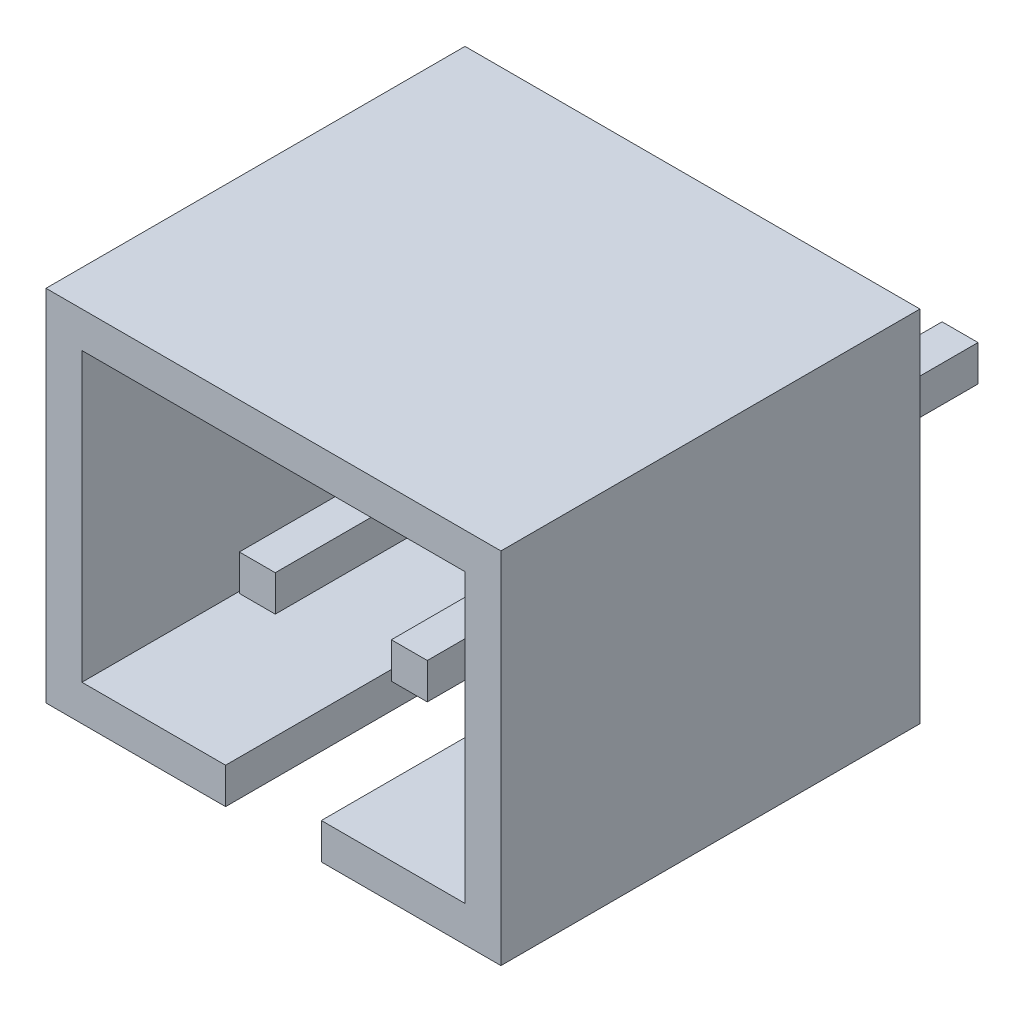
SolidWorks part; units mm, degrees
ref_plane "Front Plane" through (0, 0, 0) normal (0, 0, 1) x (1, 0, 0)
ref_plane "Top Plane" through (0, 0, 0) normal (0, 1, 0) x (1, 0, 0)
ref_plane "Right Plane" through (0, 0, 0) normal (1, 0, 0) x (0, 0, -1)
sketch "Sketch1" plane through (0, 0, 0) normal (0, 0, 1) x (1, 0, 0)
  line L1 (-3.8, 3) -> (3.8, 3)
  line L2 (-3.8, 3) -> (-3.8, -3)
  line L3 (-3.8, -3) -> (3.8, -3)
  line L4 (3.8, 3) -> (3.8, -3)
  line L5 (-3.8, 3) -> (3.8, -3) construction
  line L6 (-3.8, -3) -> (3.8, 3) construction
  point P0 (0, 0)
  dimension "D1" = 7.6
  dimension "D2" = 6
extrude "Boss-Extrude1" add sketch "Sketch1" along normal blind 1.8
sketch "Sketch2" plane through (0, 0, 1.8) normal (0, 0, 1) x (1, 0, 0)
  line L0 (-0.8, -3) -> (-0.8, -2.4)
  line L1 (-3.8, -3) -> (3.8, -3) construction
  line L2 (-0.8, -2.4) -> (-3.2, -2.4)
  line L3 (-3.2, -2.4) -> (-3.2, 2.4)
  line L4 (-3.2, 2.4) -> (3.2, 2.4)
  line L5 (0, 2.4) -> (0, 0) construction
  line L6 (-0.8, -3) -> (-3.8, -3)
  line L7 (-3.8, -3) -> (-3.8, 3)
  line L8 (-3.8, 3) -> (3.8, 3)
  line L9 (3.8, 3) -> (-3.8, 3) construction
  line L10 (3.8, -3) -> (3.8, 3)
  line L11 (0.8, -3) -> (3.8, -3)
  line L12 (0.8, -3) -> (0.8, -2.4)
  line L13 (0.8, -2.4) -> (3.2, -2.4)
  line L14 (3.2, -2.4) -> (3.2, 2.4)
  point P22 (0, 3)
  dimension "D1" = 3
  dimension "D2" = 0.6
  dimension "D3" = 0.6
  dimension "D4" = 0.6
extrude "Boss-Extrude2" add sketch "Sketch2" along normal offset from surface (5.2 mm away) 7 up to face at (0, 0, 0)
sketch "Sketch3" plane through (0, 0, 1.8) normal (0, 0, 1) x (1, 0, 0)
  line L0 (-0.8, -3) -> (0.8, -3) construction
  line L1 (-1.57, -0.2) -> (-0.97, -0.2)
  line L2 (-1.57, -0.2) -> (-1.57, -0.8)
  line L3 (-1.57, -0.8) -> (-0.97, -0.8)
  line L4 (-0.97, -0.2) -> (-0.97, -0.8)
  point P4 (-1.57, -0.5)
  point P7 (-1.27, -0.8)
  dimension "D1" = 0.6
  dimension "D2" = 2.5
  dimension "D3" = 1.27
extrude "Boss-Extrude3" add sketch "Sketch3" along normal offset from surface 6 and the other way blind 5 up to face at (0, 0, 0)
pattern_linear "LPattern1" count 2 spacing 2.54 along (1, 0, 0) of "Boss-Extrude3"
